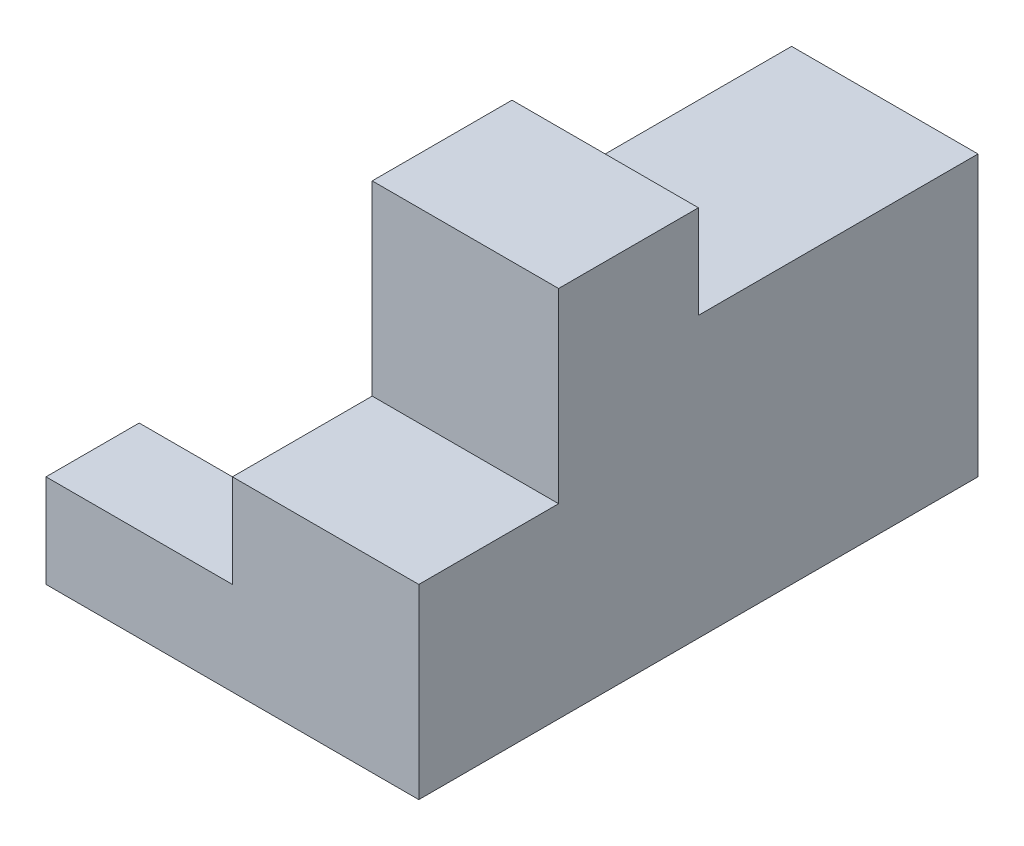
SolidWorks part; units mm, degrees
ref_plane "Front Plane" through (0, 0, 0) normal (0, 0, 1) x (1, 0, 0)
ref_plane "Top Plane" through (0, 0, 0) normal (0, 1, 0) x (1, 0, 0)
ref_plane "Right Plane" through (0, 0, 0) normal (1, 0, 0) x (0, 0, -1)
sketch "Sketch1" plane through (0, 0, 0) normal (0, 0, 1) x (1, 0, 0)
  line L1 (0, 0) -> (40, 0)
  line L2 (0, 0) -> (0, 40)
  line L3 (0, 40) -> (40, 40)
  line L4 (40, 0) -> (40, 40)
  dimension "D1" = 40
  dimension "D2" = 40
extrude "Boss-Extrude1" add sketch "Sketch1" along normal blind 60
sketch "Sketch3" plane through (0, 40, 0) normal (0, 1, 0) x (1, 0, 0)
  line L0 (0, -60) -> (0, 0) construction
  line L3 (0, -10) -> (10, -10)
  line L6 (10, -10) -> (10, -50)
  line L7 (10, -50) -> (0, -50)
  line L8 (0, -10) -> (0, -50)
extrude "Cut-Extrude1" cut sketch "Sketch3" against normal blind 60
sketch "Sketch4" plane through (0, 40, 0) normal (0, 1, 0) x (1, 0, 0)
  line L0 (40, -60) -> (0, -60) construction
  line L2 (10, -10) -> (10, -60)
  line L3 (10, -60) -> (20, -60)
  line L4 (20, -10) -> (20, -60)
  line L5 (40, 0) -> (0, 0) construction
  line L7 (20, -10) -> (20, 0)
  line L8 (20, 0) -> (10, 0)
  line L9 (10, -10) -> (10, 0)
extrude "Cut-Extrude2" cut sketch "Sketch4" against normal blind 30
sketch "Sketch5" plane through (0, 40, 0) normal (0, 1, 0) x (1, 0, 0)
  line L1 (10, 0) -> (0, 0)
  line L2 (10, 0) -> (10, -60)
  line L3 (10, -60) -> (0, -60)
  line L4 (0, 0) -> (0, -60)
extrude "Cut-Extrude3" cut sketch "Sketch5" against normal blind 30
sketch "Sketch6" plane through (0, 40, 0) normal (0, 1, 0) x (1, 0, 0)
  line L0 (20, -60) -> (20, 0) construction
  line L1 (40, 0) -> (20, 0)
  line L2 (40, 0) -> (40, -30)
  line L3 (40, -30) -> (20, -30)
  line L4 (20, 0) -> (20, -30)
extrude "Cut-Extrude4" cut sketch "Sketch6" against normal blind 10
sketch "Sketch7" plane through (0, 40, 0) normal (0, 1, 0) x (1, 0, 0)
  line L0 (20, -60) -> (20, -30) construction
  line L1 (40, -60) -> (20, -60)
  line L2 (40, -60) -> (40, -45)
  line L3 (40, -45) -> (20, -45)
  line L4 (20, -60) -> (20, -45)
extrude "Cut-Extrude5" cut sketch "Sketch7" against normal blind 20
